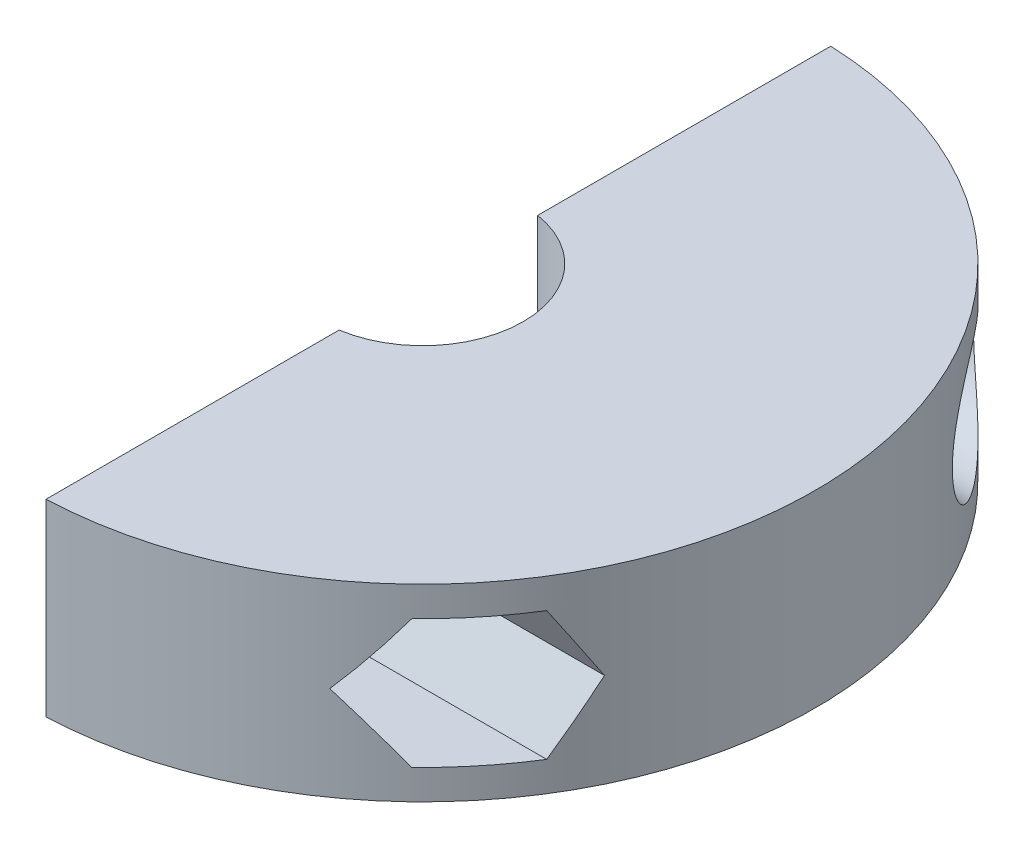
SolidWorks part; units mm, degrees
ref_plane "Спереди" through (0, 0, 0) normal (0, 0, 1) x (1, 0, 0)
ref_plane "Сверху" through (0, 0, 0) normal (0, 1, 0) x (1, 0, 0)
ref_plane "Справа" through (0, 0, 0) normal (1, 0, 0) x (0, 0, -1)
sketch "Эскиз1" plane through (0, 0, 0) normal (0, 1, 0) x (1, 0, 0)
  line L0 (0, 12.5) -> (0, -12.5)
  line L1 (0.5, 12.49) -> (0.5, -12.49)
  circle A0 centre (0, 0) radius 12.5
  circle A1 centre (0, 0) radius 3.2
  dimension "D1" = 25
  dimension "D2" = 6.4
  dimension "D3" = 0.5
extrude "Бобышка-Вытянуть1" add sketch "Эскиз1" along normal blind 6 contours A1 L1 A0
sketch "Эскиз2" plane through (0, 0, 0) normal (1, 0, 0) x (0, 0, -1)
  line L0 (12.49, 6) -> (3.1607, 0) construction
  line L2 (-3.1607, 6) -> (-12.49, 0) construction
  circle A0 centre (7.8253, 3) radius 1.1
  circle A1 centre (-7.8253, 3) radius 1.1
  dimension "D1" = 2.2
  dimension "D2" = 2.2
extrude "Вырез-Вытянуть1" cut sketch "Эскиз2" along normal through all
sketch "Эскиз3" plane through (0, 0, 0) normal (1, 0, 0) x (0, 0, -1)
  line L1 (-9.0089, 0.95) -> (-6.6418, 0.95)
  line L2 (-6.6418, 0.95) -> (-5.4582, 3)
  line L3 (-5.4582, 3) -> (-6.6418, 5.05)
  line L4 (-6.6418, 5.05) -> (-9.0089, 5.05)
  line L5 (-9.0089, 5.05) -> (-10.1925, 3)
  line L6 (-10.1925, 3) -> (-9.0089, 0.95)
  circle A0 centre (7.8253, 3) radius 2.05
  circle A1 centre (-7.8253, 3) radius 2.05 construction
  dimension "D1" = 4.1
  dimension "D2" = 4.1
extrude "Вырез-Вытянуть2" cut sketch "Эскиз3" along normal through all from offset 4
equation "\"D2@Эскиз2\"=\"D1@Эскиз2\""
equation "\"D1@Эскиз3\"=\"D2@Эскиз3\""
